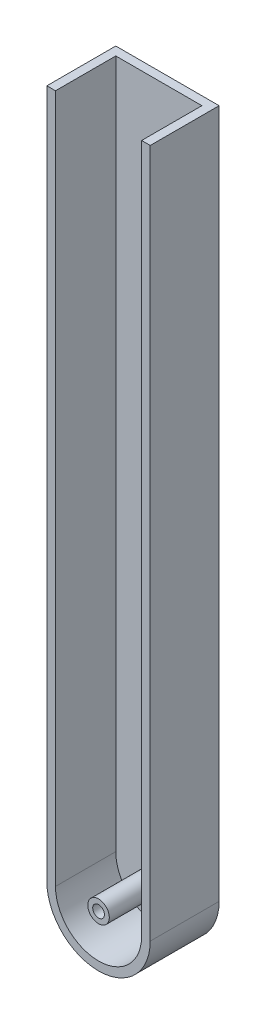
SolidWorks part; units mm, degrees
ref_plane "Front Plane" through (0, 0, 0) normal (0, 0, 1) x (1, 0, 0)
ref_plane "Top Plane" through (0, 0, 0) normal (0, 1, 0) x (1, 0, 0)
ref_plane "Right Plane" through (0, 0, 0) normal (1, 0, 0) x (0, 0, -1)
sketch "Sketch1" plane through (0, 0, 0) normal (0, 1, 0) x (1, 0, 0)
  line L1 (0, 0) -> (6.35, 0)
  line L2 (0, 0) -> (0, 50.8)
  line L3 (0, 50.8) -> (6.35, 50.8)
  line L4 (6.35, 0) -> (6.35, 50.8)
  line L5 (6.35, 50.8) -> (69.85, 50.8)
  line L6 (6.35, 50.8) -> (6.35, 44.45)
  line L7 (6.35, 44.45) -> (69.85, 44.45)
  line L8 (69.85, 50.8) -> (69.85, 44.45)
  line L9 (69.85, 50.8) -> (76.2, 50.8)
  line L10 (69.85, 50.8) -> (69.85, 0)
  line L11 (69.85, 0) -> (76.2, 0)
  line L12 (76.2, 50.8) -> (76.2, 0)
  dimension "D1" = 76.2
  dimension "D2" = 6.35
  dimension "D3" = 6.35
  dimension "D4" = 50.8
extrude "Boss-Extrude1" add sketch "Sketch1" along normal blind 508 contours L1 L4 L3 L2 | L8 L5 L4 L7 | L12 L9 L8 L10 L11
sketch "Sketch2" plane through (0, 0, 0) normal (0, -1, 0) x (1, 0, 0)
  line L0 (0, -50.8) -> (76.2, -50.8) construction
  line L1 (0, 0) -> (6.35, 0)
  line L2 (0, 0) -> (0, -50.8)
  line L3 (0, -50.8) -> (6.35, -50.8)
  line L4 (6.35, 0) -> (6.35, -50.8)
  line L5 (6.35, -44.45) -> (69.85, -44.45) construction
  line L6 (6.35, -50.8) -> (38.1, -50.8)
  line L7 (6.35, -50.8) -> (6.35, -44.45)
  line L8 (6.35, -44.45) -> (38.1, -44.45)
  line L9 (38.1, -50.8) -> (38.1, -44.45)
  dimension "D1" = 6.35
revolve "Revolve2" add sketch "Sketch2" angle 180 about L9
sketch "Sketch3" plane through (0, 0, -44.45) normal (0, 0, 1) x (1, 0, 0)
  line L0 (69.85, 508) -> (69.85, 0) construction
  line L1 (0, 0) -> (38.1, 0) construction
  circle A0 centre (38.1, 0) radius 7.9299
  arc A1 (0, 0) -> (76.2, 0) centre (38.1, 0) ccw construction
  point P0 (0, 0)
  point P4 (38.1, -17.78)
  point P6 (38.1, -0.8769)
  dimension "D1" = 31.75
extrude "Boss-Extrude2" add sketch "Sketch3" along normal up to surface (44.45 mm away) up to face at (38.1, 245.2688, 0)
sketch "Sketch4" plane through (0, 0, 0) normal (0, 0, 1) x (1, 0, 0)
  line L0 (41.3798, -7.2198) -> (34.8202, 7.2198) construction
  circle A3 centre (38.1, 0) radius 7.9299 construction
  circle A4 centre (38.1, 0) radius 4.3097
  circle A5 centre (38.1, 0) radius 7.9299 construction
extrude "Cut-Extrude1" cut sketch "Sketch4" against normal offset from surface (44.45 mm away) 6.35 up to face at (38.1, 244.475, -50.8)
